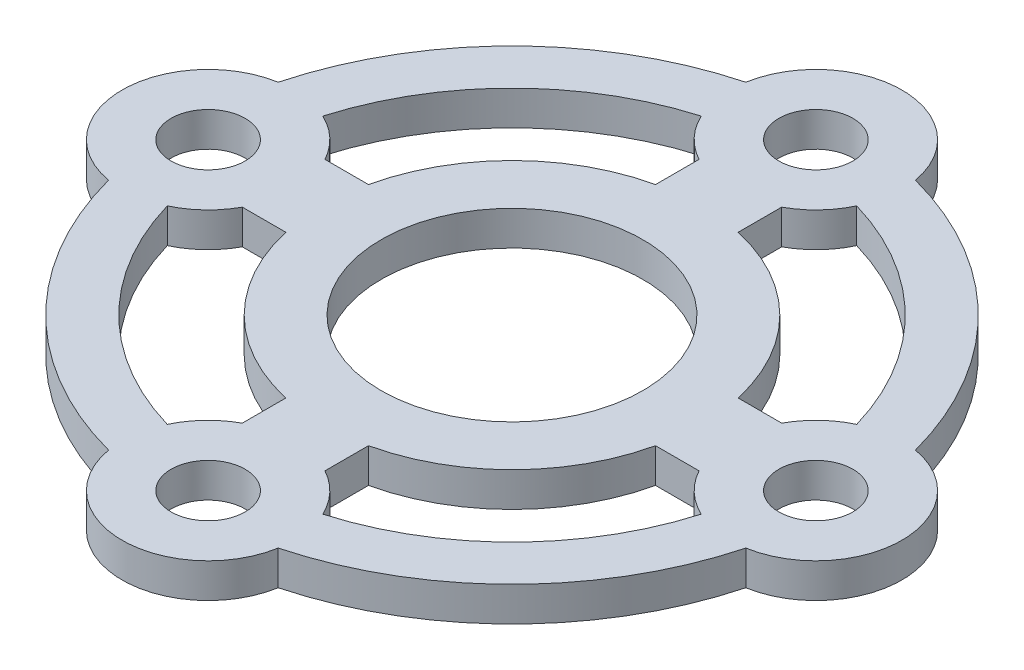
SolidWorks part; units mm, degrees
ref_plane "Front Plane" through (0, 0, 0) normal (0, 0, 1) x (1, 0, 0)
ref_plane "Top Plane" through (0, 0, 0) normal (0, 1, 0) x (1, 0, 0)
ref_plane "Right Plane" through (0, 0, 0) normal (1, 0, 0) x (0, 0, -1)
sketch "Sketch1" plane through (0, 0, 0) normal (0, 1, 0) x (1, 0, 0)
  line L0 (0, 0) -> (-17.65, 0) construction
  line L1 (17.65, 2.4) -> (-17.65, 2.4)
  line L2 (17.65, 2.4) -> (17.65, -2.4)
  line L3 (17.65, -2.4) -> (-17.65, -2.4)
  line L4 (-17.65, 2.4) -> (-17.65, -2.4)
  line L5 (17.65, 2.4) -> (-17.65, -2.4) construction
  line L6 (17.65, -2.4) -> (-17.65, 2.4) construction
  line L7 (2.4, -17.65) -> (-2.4, -17.65)
  line L8 (2.4, -17.65) -> (2.4, 17.65)
  line L9 (2.4, 17.65) -> (-2.4, 17.65)
  line L10 (-2.4, -17.65) -> (-2.4, 17.65)
  line L11 (2.4, -17.65) -> (-2.4, 17.65) construction
  line L12 (2.4, 17.65) -> (-2.4, -17.65) construction
  line L13 (0, 0) -> (-17.65, 0) construction
  line L14 (0, 0) -> (0, 17.65) construction
  line L15 (0, -19.15) -> (0, -16.15) construction
  circle A0 centre (0, 0) radius 11
  circle A1 centre (0, 0) radius 7.6
  circle A2 centre (-17.65, 0) radius 5
  circle A3 centre (0, 17.65) radius 5
  circle A4 centre (17.65, 0) radius 5
  circle A5 centre (0, -17.65) radius 5
  circle A6 centre (0, 0) radius 16.15
  circle A7 centre (0, 0) radius 19.15
  point P26 (0, -17.65)
  dimension "D1" = 22
  dimension "D2" = 15.2
  dimension "D6" = 10
  dimension "D3" = 4.8
  dimension "D4" = 17.65
  dimension "D5" = 17.65
  dimension "D8" = 90
  dimension "D9" = 3
  dimension "D7" = 4
extrude "Boss-Extrude1" add sketch "Sketch1" along normal blind 2 contours A2 L3 A0 L1 | A3 L10 A0 L8 | A4 L1 A0 L3 | A5 L8 A0 L10 | A1 | A7 | A6
hole_wizard "M4 Clearance Hole1" positions "Sketch8" profile "Sketch9" hole size "M4" standard "ANSI Metric"
sketch "Sketch8" plane through (0, 0, 0) normal (0, -1, 0) x (-1, 0, 0)
  point P0 (-17.65, 0)
  point P3 (0, 17.65)
  point P6 (17.65, 0)
  point P9 (0, -17.65)
sketch "Sketch9" plane through (17.65, 0, 0) normal (1, 0, 0) x (0, 0, -1)
  line L0 (0, 0) -> (0, 9.2919)
  line L1 (0, 9.2919) -> (2.15, 8)
  line L2 (2.15, 8) -> (2.15, 0)
  line L5 (2.15, 0) -> (0, 0)
  line L10 (0, 9.2919) -> (-2.15, 8) construction
  line L11 (0, -6.35) -> (0, 107.95) construction
  dimension "Hole Dia." = 4.3
  dimension "Hole Depth" = 8
  dimension "Drill Angle" = 118
